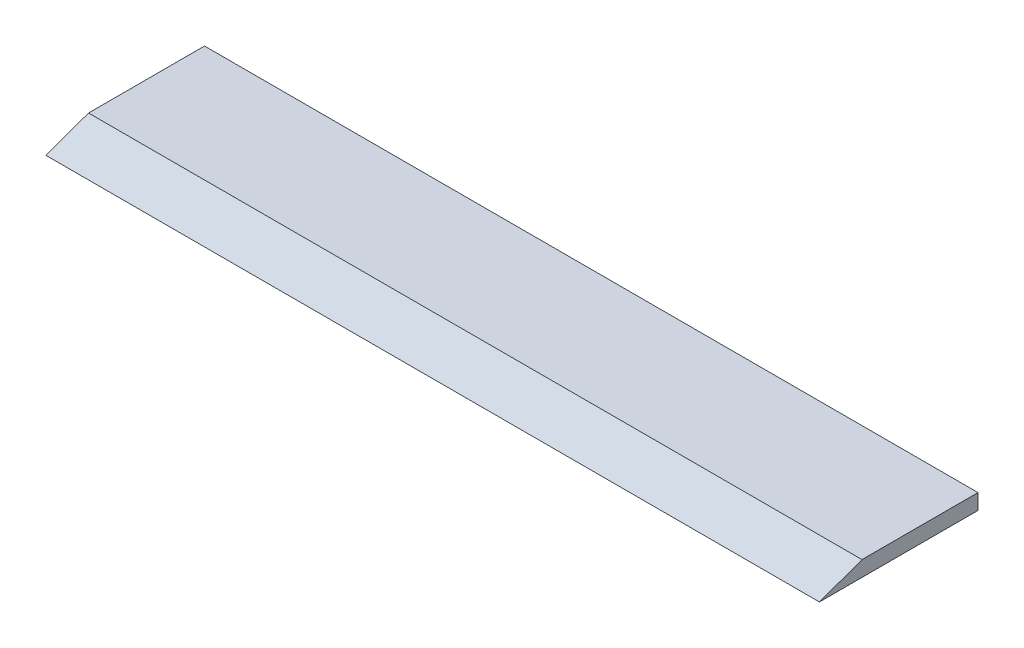
SolidWorks part; units mm, degrees
ref_plane "Alzado" through (0, 0, 0) normal (0, 0, 1) x (1, 0, 0)
ref_plane "Planta" through (0, 0, 0) normal (0, 1, 0) x (1, 0, 0)
ref_plane "Vista lateral" through (0, 0, 0) normal (1, 0, 0) x (0, 0, -1)
sketch "Croquis1" plane through (0, 0, 0) normal (1, 0, 0) x (0, 0, -1)
  line L0 (0, 0) -> (10.9899, 4)
  line L1 (0, 0) -> (40.9899, 0)
  line L3 (10.9899, 4) -> (40.9899, 4)
  line L4 (40.9899, 0) -> (40.9899, 4)
  dimension "D1" = 30
  dimension "D2" = 4
  dimension "D3" = 20
extrude "Saliente-Extruir1" add sketch "Croquis1" along normal blind 200
